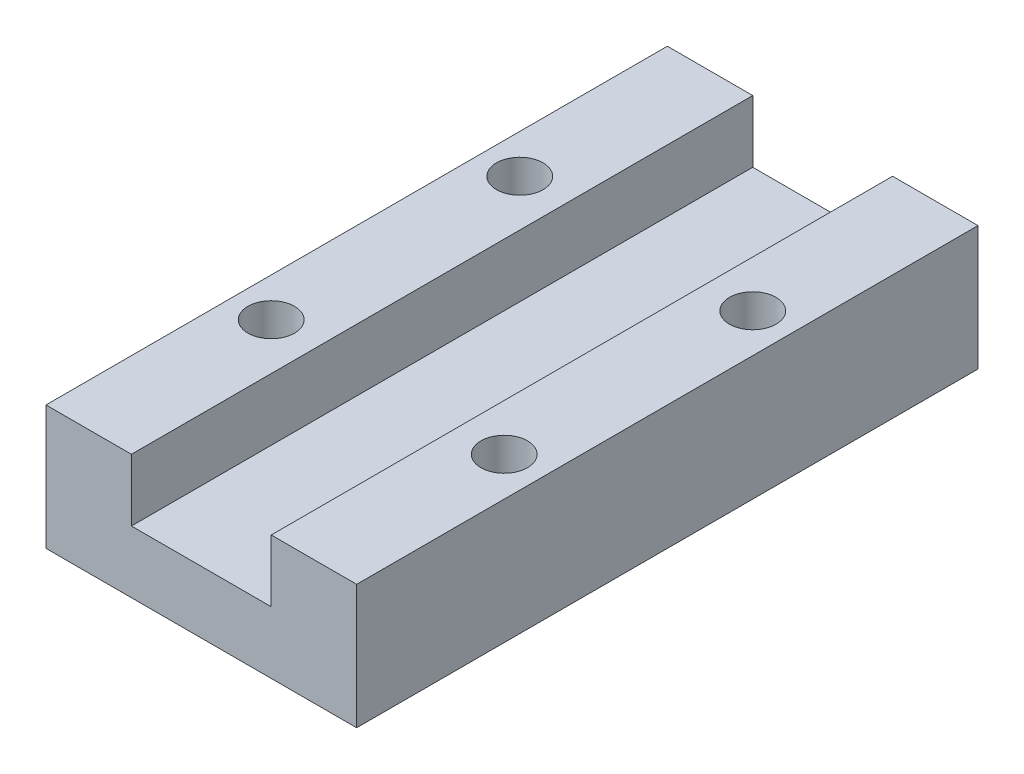
SolidWorks part; units mm, degrees
ref_plane "前视基准面" through (0, 0, 0) normal (0, 0, 1) x (1, 0, 0)
ref_plane "上视基准面" through (0, 0, 0) normal (0, 1, 0) x (1, 0, 0)
ref_plane "右视基准面" through (0, 0, 0) normal (1, 0, 0) x (0, 0, -1)
other "Configuration Table"
sketch "草图1" plane through (0, 0, 0) normal (0, 1, 0) x (1, 0, 0)
  line L1 (0, 0) -> (20, 0)
  line L2 (0, 0) -> (0, -40)
  line L3 (0, -40) -> (20, -40)
  line L4 (20, 0) -> (20, -40)
  dimension "D1" = 20
  dimension "D2" = 40
extrude "凸台-拉伸1" add sketch "草图1" along normal blind 8
sketch "草图2" plane through (0, 8, 0) normal (0, 1, 0) x (1, 0, 0)
  line L0 (0, -40) -> (20, -40) construction
  line L2 (0, 0) -> (0, -40) construction
  circle A0 centre (2.5, -28) radius 1.5
  circle A1 centre (17.5, -28) radius 1.5
  circle A2 centre (17.5, -12) radius 1.5
  circle A3 centre (2.5, -12) radius 1.5
  dimension "D1" = 3
  dimension "D4" = 12
  dimension "D5" = 2.5
  dimension "D2" = 2
  dimension "D3" = 2
extrude "切除-拉伸1" cut sketch "草图2" against normal through all
sketch "草图3" plane through (0, 8, 0) normal (0, 1, 0) x (1, 0, 0)
  line L0 (20, 0) -> (0, 0) construction
  line L1 (5.5, 0) -> (14.5, 0)
  line L2 (5.5, 0) -> (5.5, -40)
  line L3 (5.5, -40) -> (14.5, -40)
  line L4 (14.5, 0) -> (14.5, -40)
  line L5 (0, -40) -> (20, -40) construction
  line L6 (0, 0) -> (0, -40) construction
  dimension "D1" = 9
  dimension "D2" = 5.5
extrude "切除-拉伸2" cut sketch "草图3" against normal blind 4
equation "\"D4@草图2\"=20-8"
equation "\"D5@草图2\"=10-7.5"
equation "\"D2@草图3\"=10-4.5"
